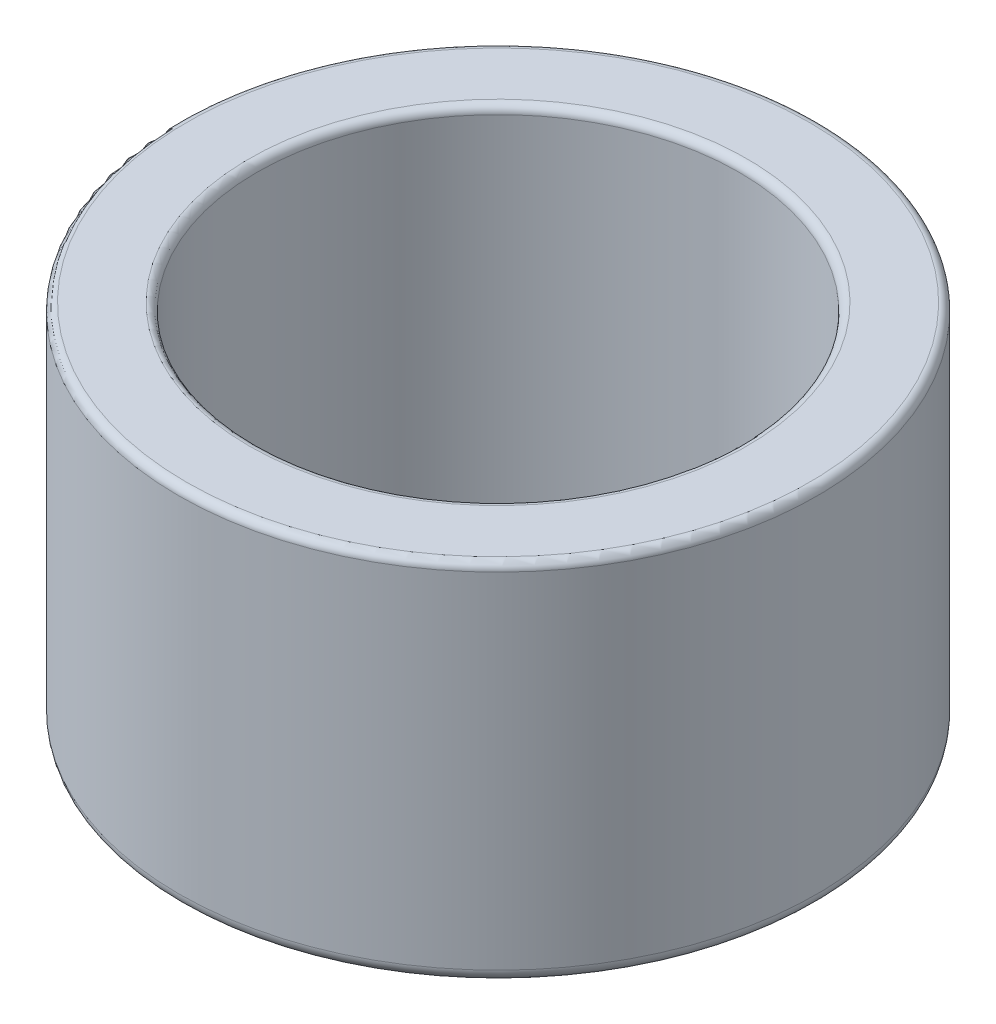
SolidWorks part; units mm, degrees
ref_plane "Front Plane" through (0, 0, 0) normal (0, 0, 1) x (1, 0, 0)
ref_plane "Top Plane" through (0, 0, 0) normal (0, 1, 0) x (1, 0, 0)
ref_plane "Right Plane" through (0, 0, 0) normal (1, 0, 0) x (0, 0, -1)
sketch "Sketch1" plane through (0, 0, 0) normal (0, 1, 0) x (1, 0, 0)
  circle A0 centre (0, 0) radius 9.231
  circle A1 centre (0, 0) radius 12.231
  dimension "D1" = 18.462
  dimension "D2" = 3
extrude "Boss-Extrude1" add sketch "Sketch1" along normal blind 14
fillet "Fillet1" radius 0.3 1 edges at (0, 14, 12.231)
fillet "Fillet5" radius 0.3 1 edges at (0, 14, 9.231)
fillet "Fillet6" radius 0.5 1 edges at (0, 0, 12.231)
fillet "Fillet7" radius 0.5 1 edges at (0, 0, 9.231)
